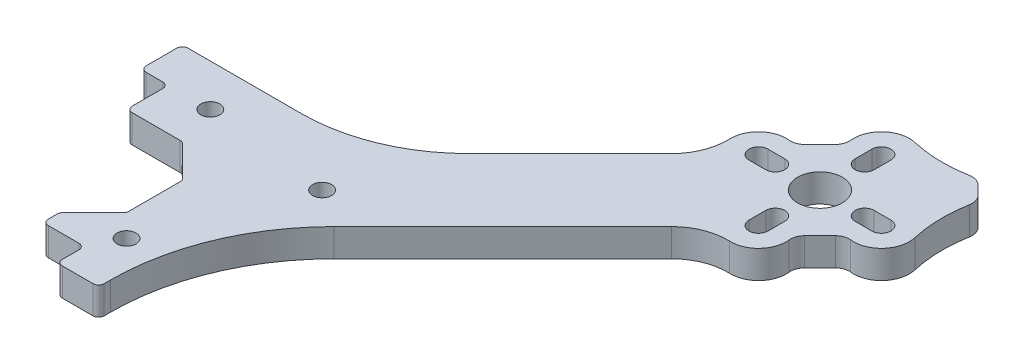
SolidWorks part; units mm, degrees
material "Thornel Mat VMA"
ref_plane "Front Plane" through (0, 0, 0) normal (0, 0, 1) x (1, 0, 0)
ref_plane "Top Plane" through (0, 0, 0) normal (0, 1, 0) x (1, 0, 0)
ref_plane "Right Plane" through (0, 0, 0) normal (1, 0, 0) x (0, 0, -1)
sketch "Sketch1" plane through (0, 0, 0) normal (0, 1, 0) x (1, 0, 0)
  line L0 (0, 37.5) -> (0, 45)
  line L4 (30, -2.1177) -> (30, 2.1177) construction
  line L5 (0, 45) -> (21.2599, 45)
  line L7 (30, 0) -> (22.5, 0)
  line L8 (22.5, 0) -> (22.5, 5)
  line L9 (22.5, 5) -> (15, 5)
  line L10 (15, 5) -> (15, 30)
  line L11 (5, 30) -> (15, 30)
  line L12 (5, 37.5) -> (5, 30)
  line L13 (0, 37.5) -> (5, 37.5)
  line L15 (0, 0) -> (79.5495, 79.5495) construction
  line L16 (30, 0) -> (30, 2.1177)
  line L17 (42.4731, 53.7868) -> (60.6301, 71.9438)
  line L18 (71.9438, 60.6301) -> (41.7157, 30.402)
  line L19 (79.5495, 87.5495) -> (79.5495, 71.5495) construction
  line L20 (79.5495, 87.5495) -> (79.5495, 90.5495) construction
  line L21 (77.8495, 87.5495) -> (77.8495, 90.5495)
  line L22 (81.2495, 87.5495) -> (81.2495, 90.5495)
  line L23 (87.5495, 79.5495) -> (90.5495, 79.5495) construction
  line L24 (87.5495, 81.2495) -> (90.5495, 81.2495)
  line L25 (87.5495, 77.8495) -> (90.5495, 77.8495)
  line L26 (79.5495, 71.5495) -> (79.5495, 68.5495) construction
  line L27 (81.2495, 71.5495) -> (81.2495, 68.5495)
  line L28 (77.8495, 71.5495) -> (77.8495, 68.5495)
  line L29 (71.5495, 79.5495) -> (68.5495, 79.5495) construction
  line L30 (71.5495, 77.8495) -> (68.5495, 77.8495)
  line L31 (71.5495, 81.2495) -> (68.5495, 81.2495)
  line L32 (71.0988, 85.2409) -> (73.8581, 88.0002)
  line L33 (85.2409, 71.0988) -> (88.0002, 73.8581)
  line L34 (91.9239, 95.4594) -> (95.4594, 91.9239)
  line L35 (93.6916, 93.6916) -> (79.5495, 79.5495) construction
  arc A0 (30, 2.1177) -> (41.7157, 30.402) centre (70, 2.1177) cw
  circle A1 centre (79.5495, 79.5495) radius 4
  arc A2 (77.8495, 87.5495) -> (81.2495, 87.5495) centre (79.5495, 87.5495) ccw
  arc A3 (81.2495, 90.5495) -> (77.8495, 90.5495) centre (79.5495, 90.5495) ccw
  arc A4 (87.5495, 81.2495) -> (87.5495, 77.8495) centre (87.5495, 79.5495) ccw
  arc A5 (90.5495, 77.8495) -> (90.5495, 81.2495) centre (90.5495, 79.5495) ccw
  arc A6 (81.2495, 71.5495) -> (77.8495, 71.5495) centre (79.5495, 71.5495) ccw
  arc A7 (77.8495, 68.5495) -> (81.2495, 68.5495) centre (79.5495, 68.5495) ccw
  arc A8 (71.5495, 77.8495) -> (71.5495, 81.2495) centre (71.5495, 79.5495) ccw
  arc A9 (68.5495, 81.2495) -> (68.5495, 77.8495) centre (68.5495, 79.5495) ccw
  arc A10 (63.5527, 79.3713) -> (69.0705, 84.5223) centre (68.5495, 79.5495) cw
  arc A11 (74.5767, 90.0285) -> (80.6607, 95.4245) centre (79.5495, 90.5495) cw
  arc A12 (80.6607, 95.4245) -> (91.9239, 95.4594) centre (86.2167, 119.7993) ccw
  arc A13 (69.0705, 84.5223) -> (71.0988, 85.2409) centre (69.331, 87.0087) ccw
  arc A14 (63.5527, 79.3713) -> (60.6301, 71.9438) centre (53.559, 79.0149) cw
  arc A15 (73.8581, 88.0002) -> (74.5767, 90.0285) centre (72.0903, 89.768) ccw
  arc A16 (95.4245, 80.6607) -> (95.4594, 91.9239) centre (119.7993, 86.2167) cw
  arc A17 (90.0285, 74.5767) -> (95.4245, 80.6607) centre (90.5495, 79.5495) ccw
  arc A18 (88.0002, 73.8581) -> (90.0285, 74.5767) centre (89.768, 72.0903) cw
  arc A19 (84.5223, 69.0705) -> (85.2409, 71.0988) centre (87.0087, 69.331) cw
  arc A20 (79.3713, 63.5527) -> (84.5223, 69.0705) centre (79.5495, 68.5495) ccw
  arc A21 (79.3713, 63.5527) -> (71.9438, 60.6301) centre (79.0149, 53.559) ccw
  arc A22 (21.2599, 45) -> (42.4731, 53.7868) centre (21.2599, 75) ccw
  point P0 (0, 0)
  point P14 (10.6299, 45)
  point P21 (79.5495, 89.0495)
  point P29 (79.5495, 79.5495)
  point P33 (89.0495, 79.5495)
  point P40 (79.5495, 70.0495)
  point P47 (70.0495, 79.5495)
  point P54 (79.5495, 79.5495)
  dimension "D11" = 8
  dimension "D13" = 1.7
  dimension "D17" = 5
  dimension "D18" = 25
  dimension "D22" = 2.5
  dimension "D23" = 10
  dimension "D24" = 30
  dimension "D26" = 40
  dimension "D3" = 30
  dimension "D4" = 8
  dimension "D5" = 7.5
  dimension "D6" = 15
  dimension "D7" = 5
  dimension "D8" = 45
  dimension "D9" = 112.5
  dimension "D10" = 45
  dimension "D12" = 45
  dimension "D14" = 3
  dimension "D15" = 8
  dimension "D19" = 20
  dimension "D20" = 2.5
  dimension "D21" = 10
  dimension "D25" = 15
  dimension "D16" = 4
extrude "Boss-Extrude1" add sketch "Sketch1" along normal mid plane 5
sketch "Sketch2" plane through (0, 2.5, 0) normal (0, 1, 0) x (1, 0, 0)
  line L0 (15, 30) -> (21, 24)
  line L1 (21, 24) -> (21, 14)
  line L2 (21, 14) -> (15, 8)
  line L15 (21.2599, 45) -> (0, 45)
  line L16 (0, 45) -> (0, 37.5)
  line L17 (0, 37.5) -> (5, 37.5)
  line L18 (5, 37.5) -> (5, 30)
  line L19 (5, 30) -> (15, 30)
  line L20 (15, 30) -> (15, 5)
  line L21 (15, 5) -> (22.5, 5)
  line L22 (22.5, 5) -> (22.5, 0)
  line L23 (22.5, 0) -> (30, 0)
  line L24 (30, 0) -> (30, 2.1177)
  line L25 (41.7157, 30.402) -> (71.9438, 60.6301)
  line L26 (85.2409, 71.0988) -> (88.0002, 73.8581)
  line L27 (95.4594, 91.9239) -> (91.9239, 95.4594)
  line L28 (73.8581, 88.0002) -> (71.0988, 85.2409)
  line L29 (60.6301, 71.9438) -> (42.4731, 53.7868)
  line L30 (21.2599, 45) -> (0, 45)
  line L31 (0, 45) -> (0, 37.5)
  line L32 (0, 37.5) -> (5, 37.5)
  line L33 (5, 37.5) -> (5, 30)
  line L34 (5, 30) -> (15, 30)
  line L35 (15, 30) -> (15, 5)
  line L36 (15, 5) -> (22.5, 5)
  line L37 (22.5, 5) -> (22.5, 0)
  line L38 (22.5, 0) -> (30, 0)
  line L39 (30, 0) -> (30, 2.1177)
  line L40 (41.7157, 30.402) -> (71.9438, 60.6301)
  line L41 (85.2409, 71.0988) -> (88.0002, 73.8581)
  line L42 (95.4594, 91.9239) -> (91.9239, 95.4594)
  line L43 (73.8581, 88.0002) -> (71.0988, 85.2409)
  line L44 (60.6301, 71.9438) -> (42.4731, 53.7868)
  arc A14 (21.2599, 45) -> (42.4731, 53.7868) centre (21.2599, 75) ccw
  arc A15 (41.7157, 30.402) -> (30, 2.1177) centre (70, 2.1177) ccw
  arc A16 (79.3713, 63.5527) -> (71.9438, 60.6301) centre (79.0149, 53.559) ccw
  arc A17 (79.3713, 63.5527) -> (84.5223, 69.0705) centre (79.5495, 68.5495) ccw
  arc A18 (85.2409, 71.0988) -> (84.5223, 69.0705) centre (87.0087, 69.331) ccw
  arc A19 (90.0285, 74.5767) -> (88.0002, 73.8581) centre (89.768, 72.0903) ccw
  arc A20 (90.0285, 74.5767) -> (95.4245, 80.6607) centre (90.5495, 79.5495) ccw
  arc A21 (95.4594, 91.9239) -> (95.4245, 80.6607) centre (119.7993, 86.2167) ccw
  arc A22 (80.6607, 95.4245) -> (91.9239, 95.4594) centre (86.2167, 119.7993) ccw
  arc A23 (80.6607, 95.4245) -> (74.5767, 90.0285) centre (79.5495, 90.5495) ccw
  arc A24 (73.8581, 88.0002) -> (74.5767, 90.0285) centre (72.0903, 89.768) ccw
  arc A25 (69.0705, 84.5223) -> (71.0988, 85.2409) centre (69.331, 87.0087) ccw
  arc A26 (69.0705, 84.5223) -> (63.5527, 79.3713) centre (68.5495, 79.5495) ccw
  arc A27 (60.6301, 71.9438) -> (63.5527, 79.3713) centre (53.559, 79.0149) ccw
  arc A28 (21.2599, 45) -> (42.4731, 53.7868) centre (21.2599, 75) ccw
  arc A29 (41.7157, 30.402) -> (30, 2.1177) centre (70, 2.1177) ccw
  arc A30 (79.3713, 63.5527) -> (71.9438, 60.6301) centre (79.0149, 53.559) ccw
  arc A31 (79.3713, 63.5527) -> (84.5223, 69.0705) centre (79.5495, 68.5495) ccw
  arc A32 (85.2409, 71.0988) -> (84.5223, 69.0705) centre (87.0087, 69.331) ccw
  arc A33 (90.0285, 74.5767) -> (88.0002, 73.8581) centre (89.768, 72.0903) ccw
  arc A34 (90.0285, 74.5767) -> (95.4245, 80.6607) centre (90.5495, 79.5495) ccw
  arc A35 (95.4594, 91.9239) -> (95.4245, 80.6607) centre (119.7993, 86.2167) ccw
  arc A36 (80.6607, 95.4245) -> (91.9239, 95.4594) centre (86.2167, 119.7993) ccw
  arc A37 (80.6607, 95.4245) -> (74.5767, 90.0285) centre (79.5495, 90.5495) ccw
  arc A38 (73.8581, 88.0002) -> (74.5767, 90.0285) centre (72.0903, 89.768) ccw
  arc A39 (69.0705, 84.5223) -> (71.0988, 85.2409) centre (69.331, 87.0087) ccw
  arc A40 (69.0705, 84.5223) -> (63.5527, 79.3713) centre (68.5495, 79.5495) ccw
  arc A41 (60.6301, 71.9438) -> (63.5527, 79.3713) centre (53.559, 79.0149) ccw
  line M39 (15, 30) -> (15, 5)
  dimension "D2" = 135
  dimension "D3" = 6
  dimension "D4" = 3
  dimension "D1" = 0
extrude "Cut-Extrude1" cut sketch "Sketch2" against normal blind 10 contours L2 L1 L0 M39
fillet "Fillet1" radius 2.5 2 edges at (95.4594, 0, -91.9239) (91.9239, 0, -95.4594)
fillet "Fillet2" radius 1 12 edges at (22.5, 0, 0) (22.5, 0, -5) (15, 0, -5) (5, 0, -30) (5, 0, -37.5) (30, 0, 0) (0, 0, -45) (0, 0, -37.5) (15, 0, -8) (21, 0, -14) (21, 0, -24) (15, 0, -30)
hole_wizard "M3 Clearance Hole1" positions "Sketch3" profile "Sketch4" hole size "M3" standard "ANSI Metric" end condition through all
sketch "Sketch3" plane through (0, 2.5, 0) normal (0, 1, 0) x (1, 0, 0)
  point P1 (35, 35)
  dimension "D1" = 35
  dimension "D2" = 35
sketch "Sketch4" plane through (35, 2.5, -35) normal (1, 0, 0) x (0, 0, 1)
  line L0 (0, 0) -> (0, 5)
  line L1 (0, 5) -> (1.7, 5)
  line L2 (1.7, 5) -> (1.7, 0)
  line L5 (1.7, 0) -> (0, 0)
  line L11 (0, -6.35) -> (0, 107.95) construction
  dimension "Thru Hole Dia." = 3.4
  dimension "Thru Hole Depth" = 5
hole_wizard "M3 Clearance Hole2" positions "Sketch5" profile "Sketch6" hole size "M3" standard "ANSI Metric" end condition through all
sketch "Sketch5" plane through (0, 2.5, 0) normal (0, 1, 0) x (1, 0, 0)
  line L0 (1, 37.5) -> (4, 37.5) construction
  line L1 (5, 36.5) -> (5, 31) construction
  line L2 (29, 0) -> (23.5, 0) construction
  line L3 (30, 1) -> (30, 2.1177) construction
  point P0 (12.5, 37.5)
  point P2 (25, 10)
  point P14 (30, 1.5589)
  point P18 (0, 0)
  dimension "D1" = 7.5
  dimension "D2" = 10
  dimension "D3" = 5
sketch "Sketch6" plane through (12.5, 2.5, -37.5) normal (1, 0, 0) x (0, 0, 1)
  line L0 (0, 0) -> (0, 5)
  line L1 (0, 5) -> (1.7, 5)
  line L2 (1.7, 5) -> (1.7, 0)
  line L5 (1.7, 0) -> (0, 0)
  line L11 (0, -6.35) -> (0, 107.95) construction
  dimension "Thru Hole Dia." = 3.4
  dimension "Thru Hole Depth" = 5
